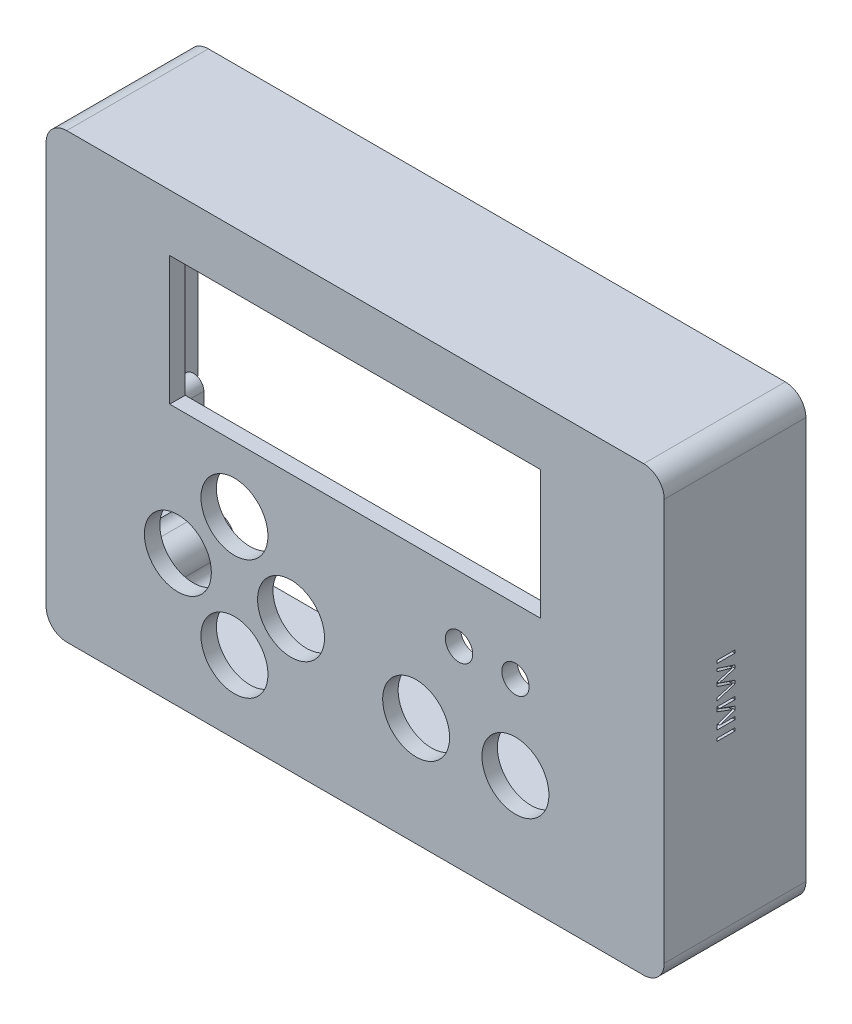
SolidWorks part; units mm, degrees
ref_plane "Front Plane" through (0, 0, 0) normal (0, 0, 1) x (1, 0, 0)
ref_plane "Top Plane" through (0, 0, 0) normal (0, 1, 0) x (1, 0, 0)
ref_plane "Right Plane" through (0, 0, 0) normal (1, 0, 0) x (0, 0, -1)
sketch "Sketch2" plane through (0, 0, 0) normal (0, 0, 1) x (1, 0, 0)
  line L0 (-36, 7) -> (36, 32) construction
  line L1 (-56, -43) -> (56, -43)
  line L2 (-60, -39) -> (-60, 39)
  line L3 (-56, 43) -> (56, 43)
  line L4 (60, -39) -> (60, 39)
  line L5 (-60, -43) -> (60, 43) construction
  line L7 (-36, 32) -> (36, 32)
  line L8 (-36, 32) -> (-36, 7)
  line L9 (-36, 7) -> (36, 7)
  line L10 (36, 32) -> (36, 7)
  line L11 (0, 43) -> (0, -43) construction
  line L12 (-23.4344, -5.6413) -> (-12.4484, -17.2736) construction
  line L13 (-12.4484, -17.2736) -> (-23.4344, -28.9058) construction
  line L14 (-23.4344, -28.9058) -> (-34.4203, -17.2736) construction
  line L15 (-34.4203, -17.2736) -> (-23.4344, -5.6413) construction
  line L16 (-23.4344, -5.6413) -> (-23.4344, -28.9058) construction
  line L17 (-12.4484, -17.2736) -> (-34.4203, -17.2736) construction
  circle A0 centre (-23.4344, -5.6413) radius 6.5
  circle A1 centre (-12.4484, -17.2736) radius 6.5
  circle A2 centre (-34.4203, -17.2736) radius 6.5
  circle A3 centre (-23.4344, -28.9058) radius 6.5
  circle A4 centre (11.8343, -21.8914) radius 6.5
  circle A5 centre (31.1116, -21.8914) radius 6.5
  circle A6 centre (20.1586, -5.6413) radius 2.65
  circle A7 centre (31.1116, -5.6413) radius 2.65
  arc A8 (-56, -43) -> (-60, -39) centre (-56, -39) cw
  arc A9 (56, -43) -> (60, -39) centre (56, -39) ccw
  arc A10 (56, 43) -> (60, 39) centre (56, 39) cw
  arc A11 (-60, 39) -> (-56, 43) centre (-56, 39) cw
  point P0 (0, 0)
  point P20 (0, 19.5)
  point P29 (0, 0)
  point P30 (0, 0)
  point P46 (60, -43)
  dimension "D3" = 72
  dimension "D6" = 11
  dimension "D7" = 4
  dimension "D1" = 86
  dimension "D2" = 120
  dimension "D4" = 25
  dimension "D5" = 16
extrude "Boss-Extrude1" add sketch "Sketch2" along normal blind 2.5
sketch "Sketch3" plane through (0, 0, 0) normal (0, 0, -1) x (-1, 0, 0)
  line L0 (60, 39) -> (60, -39) construction
  line L1 (56, -43) -> (-56, -43) construction
  line L2 (-60, -39) -> (-60, 39) construction
  line L3 (-56, 43) -> (56, 43) construction
  line L4 (60, 39) -> (60, -39)
  line L5 (56, -43) -> (-56, -43)
  line L6 (-60, -39) -> (-60, 39)
  line L7 (-56, 43) -> (56, 43)
  line L9 (-54, 41) -> (54, 41)
  line L10 (-58, 37) -> (-58, -37)
  line L11 (-54, -41) -> (54, -41)
  line L12 (58, 37) -> (58, -37)
  line L13 (-58, 41) -> (58, -41) construction
  line L14 (-58, -41) -> (58, 41) construction
  arc A0 (60, 39) -> (56, 43) centre (56, 39) ccw construction
  arc A1 (56, -43) -> (60, -39) centre (56, -39) ccw construction
  arc A2 (-60, -39) -> (-56, -43) centre (-56, -39) ccw construction
  arc A3 (-56, 43) -> (-60, 39) centre (-56, 39) ccw construction
  arc A4 (60, 39) -> (56, 43) centre (56, 39) ccw
  arc A5 (56, -43) -> (60, -39) centre (56, -39) ccw
  arc A6 (-60, -39) -> (-56, -43) centre (-56, -39) ccw
  arc A7 (-56, 43) -> (-60, 39) centre (-56, 39) ccw
  arc A8 (-58, 37) -> (-54, 41) centre (-54, 37) cw
  arc A9 (-58, -37) -> (-54, -41) centre (-54, -37) ccw
  arc A10 (58, -37) -> (54, -41) centre (54, -37) cw
  arc A11 (54, 41) -> (58, 37) centre (54, 37) cw
  point P3 (0, 0)
  dimension "D5" = 4
  dimension "D1" = 2
  dimension "D2" = 2
  dimension "D3" = 2
  dimension "D4" = 2
extrude "Boss-Extrude2" add sketch "Sketch3" along normal blind 25
sketch "Sketch5" plane through (0, 0, 0) normal (0, 0, -1) x (-1, 0, 0)
  line L0 (-36, 7) -> (-36, 32) construction
  line L1 (36, 7) -> (-36, 7) construction
  line L2 (36, 32) -> (36, 7) construction
  line L3 (-36, 32) -> (36, 32) construction
  line L4 (-36, 7) -> (-36, 32)
  line L5 (36, 7) -> (-36, 7)
  line L6 (36, 32) -> (36, 7)
  line L7 (-36, 32) -> (36, 32)
  line L9 (-37, 33) -> (37, 33)
  line L10 (-37, 33) -> (-37, 6)
  line L11 (-37, 6) -> (37, 6)
  line L12 (37, 33) -> (37, 6)
  circle A0 centre (23.4344, -28.9058) radius 6.5 construction
  circle A1 centre (34.4203, -17.2736) radius 6.5 construction
  circle A2 centre (23.4344, -5.6413) radius 6.5 construction
  circle A3 centre (12.4484, -17.2736) radius 6.5 construction
  circle A4 centre (-11.8343, -21.8914) radius 6.5 construction
  circle A5 centre (-20.1586, -5.6413) radius 2.65 construction
  circle A6 centre (-31.1116, -5.6413) radius 2.65 construction
  circle A7 centre (-31.1116, -21.8914) radius 6.5 construction
  circle A8 centre (23.4344, -28.9058) radius 6.5
  circle A9 centre (34.4203, -17.2736) radius 6.5
  circle A10 centre (23.4344, -5.6413) radius 6.5
  circle A11 centre (12.4484, -17.2736) radius 6.5
  circle A12 centre (-11.8343, -21.8914) radius 6.5
  circle A13 centre (-20.1586, -5.6413) radius 2.65
  circle A14 centre (-31.1116, -5.6413) radius 2.65
  circle A15 centre (-31.1116, -21.8914) radius 6.5
  circle A16 centre (-31.1116, -5.6413) radius 3.75
  circle A17 centre (-20.1586, -5.6413) radius 3.75
  circle A18 centre (-31.1116, -21.8914) radius 7.5
  circle A19 centre (-11.8343, -21.8914) radius 7.5
  circle A20 centre (12.4484, -17.2736) radius 7.5
  circle A21 centre (23.4344, -5.6413) radius 7.5
  circle A22 centre (34.4203, -17.2736) radius 7.5
  circle A23 centre (23.4344, -28.9058) radius 7.5
  dimension "D1" = 1
  dimension "D2" = 1
  dimension "D3" = 1
  dimension "D4" = 1
extrude "Boss-Extrude3" add sketch "Sketch5" along normal blind 0.5
sketch "Sketch6" plane through (0, 0, 0) normal (0, 0, -1) x (-1, 0, 0)
  line L0 (37.875, 41) -> (37.875, -41) construction
  line L1 (54, 41) -> (-54, 41) construction
  line L2 (-54, -41) -> (54, -41) construction
  line L3 (-37.875, -41) -> (-37.875, 41) construction
  line L4 (0, 41) -> (0, -39.2896) construction
  line L5 (37.875, 35) -> (37.875, 37) construction
  line L6 (37.125, 35) -> (37.125, 37)
  line L7 (38.625, 35) -> (38.625, 37)
  line L9 (-34.4881, 20) -> (37.5119, 20) construction
  line L12 (37.875, 38) -> (37.875, 34) construction
  line L13 (39.875, 38) -> (39.875, 34)
  line L14 (35.875, 38) -> (35.875, 34)
  line L15 (37.875, 2) -> (37.875, 6) construction
  line L16 (39.875, 2) -> (39.875, 6)
  line L17 (35.875, 2) -> (35.875, 6)
  line L18 (37.875, 5) -> (37.875, 3) construction
  line L19 (37.125, 5) -> (37.125, 3)
  line L20 (38.625, 5) -> (38.625, 3)
  line L21 (-37.875, 5) -> (-37.875, 3) construction
  line L22 (-37.125, 5) -> (-37.125, 3)
  line L23 (-38.625, 5) -> (-38.625, 3)
  line L24 (-37.875, 2) -> (-37.875, 6) construction
  line L25 (-39.875, 2) -> (-39.875, 6)
  line L26 (-35.875, 2) -> (-35.875, 6)
  line L27 (-37.875, 35) -> (-37.875, 37) construction
  line L28 (-37.125, 35) -> (-37.125, 37)
  line L29 (-38.625, 35) -> (-38.625, 37)
  line L30 (-37.875, 38) -> (-37.875, 34) construction
  line L31 (-39.875, 38) -> (-39.875, 34)
  line L32 (-35.875, 38) -> (-35.875, 34)
  line L33 (-36, 32) -> (36, 32) construction
  line L34 (36, 7) -> (-36, 7) construction
  arc A0 (37.125, 35) -> (38.625, 35) centre (37.875, 35) ccw
  arc A1 (38.625, 37) -> (37.125, 37) centre (37.875, 37) ccw
  arc A2 (39.875, 38) -> (35.875, 38) centre (37.875, 38) ccw
  arc A3 (35.875, 34) -> (39.875, 34) centre (37.875, 34) ccw
  arc A4 (39.875, 2) -> (35.875, 2) centre (37.875, 2) cw
  arc A5 (35.875, 6) -> (39.875, 6) centre (37.875, 6) cw
  arc A6 (37.125, 5) -> (38.625, 5) centre (37.875, 5) cw
  arc A7 (38.625, 3) -> (37.125, 3) centre (37.875, 3) cw
  arc A8 (-37.125, 5) -> (-38.625, 5) centre (-37.875, 5) ccw
  arc A9 (-38.625, 3) -> (-37.125, 3) centre (-37.875, 3) ccw
  arc A10 (-39.875, 2) -> (-35.875, 2) centre (-37.875, 2) ccw
  arc A11 (-35.875, 6) -> (-39.875, 6) centre (-37.875, 6) ccw
  arc A12 (-37.125, 35) -> (-38.625, 35) centre (-37.875, 35) cw
  arc A13 (-38.625, 37) -> (-37.125, 37) centre (-37.875, 37) cw
  arc A14 (-39.875, 38) -> (-35.875, 38) centre (-37.875, 38) cw
  arc A15 (-35.875, 34) -> (-39.875, 34) centre (-37.875, 34) cw
  point P12 (37.875, 36)
  point P25 (37.875, 36)
  point P32 (37.875, 4)
  point P39 (37.875, 4)
  point P46 (-37.875, 4)
  point P53 (-37.875, 4)
  point P60 (-37.875, 36)
  point P67 (-37.875, 36)
  dimension "D4" = 0.75
  dimension "D5" = 2
  dimension "D1" = 75.75
  dimension "D2" = 37.875
  dimension "D3" = 2
  dimension "D6" = 4
  dimension "D7" = 4
  dimension "D8" = 3
extrude "Boss-Extrude4" add sketch "Sketch6" along normal blind 4
sketch "Sketch7" plane through (0, 0, 0) normal (0, 0, -1) x (-1, 0, 0)
  line L0 (0, 41) -> (0, -41) construction
  line L1 (54, 41) -> (-54, 41) construction
  line L2 (-54, -41) -> (54, -41) construction
  line L3 (-58, 0) -> (58, 0) construction
  line L4 (-58, 37) -> (-58, -37) construction
  line L5 (58, -37) -> (58, 37) construction
  line L6 (54, 41) -> (-54, 41) construction
  line L7 (58, -37) -> (58, 37)
  line L8 (54, 41) -> (-54, 41)
  line L9 (-58, -37) -> (-58, 37)
  circle A0 centre (54.5, 37.5) radius 1.7
  arc A1 (53.3, 41) -> (58, 36.3) centre (54.5, 37.5) ccw
  arc A2 (58, 37) -> (54, 41) centre (54, 37) ccw construction
  arc A3 (58, 37) -> (54, 41) centre (54, 37) ccw
  circle A4 centre (54.5, -37.5) radius 1.7
  arc A5 (53.3, -41) -> (58, -36.3) centre (54.5, -37.5) cw
  arc A6 (-53.3, -41) -> (-58, -36.3) centre (-54.5, -37.5) ccw
  circle A7 centre (-54.5, -37.5) radius 1.7
  arc A8 (-58, 37) -> (-54, 41) centre (-54, 37) cw
  arc A9 (-53.3, 41) -> (-58, 36.3) centre (-54.5, 37.5) cw
  circle A10 centre (-54.5, 37.5) radius 1.7
  arc A11 (54, -41) -> (58, -37) centre (54, -37) ccw construction
  arc A12 (-58, -37) -> (-54, -41) centre (-54, -37) ccw construction
  arc A13 (54, -41) -> (58, -37) centre (54, -37) ccw
  arc A14 (-58, -37) -> (-54, -41) centre (-54, -37) ccw
  point P15 (54.301, 37.6033)
  arc M8 (-54, 41) -> (-58, 37) centre (-54, 37) ccw
  line M9 (-58, 37) -> (-58, -37)
  arc M10 (-58, -37) -> (-54, -41) centre (-54, -37) ccw
  line M11 (-54, -41) -> (54, -41)
  arc M12 (54, -41) -> (58, -37) centre (54, -37) ccw
  line M13 (58, -37) -> (58, 37)
  arc M14 (58, 37) -> (54, 41) centre (54, 37) ccw
  line M15 (54, 41) -> (-54, 41)
  dimension "D1" = 54.5
  dimension "D2" = 37.5
extrude "Boss-Extrude6" add sketch "Sketch7" along normal up to surface (25 mm away) contours A5 A4 M11 M12 M13 | A1 L7 A0 M15 M14 | A9 A10 M15 M8 M9 | A6 L9 A7 M11 M10 up to face at (0, 0, -25)
fillet "Fillet2" radius 2 8 edges at (-53.3, -41, -12.5) (-58, -36.3, -12.5) (53.3, -41, -12.5) (58, -36.3, -12.5) (53.3, 41, -12.5) (58, 36.3, -12.5) (-53.3, 41, -12.5) (-58, 36.3, -12.5)
sketch "Sketch8" plane through (-60, 0, 0) normal (-1, 0, 0) x (0, 0, 1)
  line L0 (-25, -39) -> (-25, 39) construction
  line L1 (-25, -33) -> (-15, -33)
  line L2 (-25, -33) -> (-25, -13)
  line L3 (-25, -13) -> (-15, -13)
  line L4 (-15, -33) -> (-15, -13)
  line L5 (2.5, -43) -> (-25, -43) construction
  dimension "D1" = 20
  dimension "D2" = 10
  dimension "D3" = 10
extrude "Cut-Extrude1" cut sketch "Sketch8" against normal up to next
sketch "Sketch9" plane through (60, 0, 0) normal (1, 0, 0) x (0, 0, -1)
  line L0 (11.25, -39) -> (11.25, 39) construction
  line L1 (-2.5, -39) -> (25, -39) construction
  line L2 (-2.5, 39) -> (25, 39) construction
  text T0 "IMWI" font "Century Gothic" height 3.5
  point P3 (15.4983, 12.9039)
  point P4 (16.0515, -16.6346)
  point P5 (11.4294, 28.6507)
  point P6 (12.2848, -4.235)
  point P7 (12.2278, -24.3219)
  point P8 (12.4022, -13.392)
  point P9 (12.447, 12.6028)
  point P10 (12.4644, 4.1349)
  point P11 (12.5605, 5.3166)
  point P12 (13.8206, -21.1347)
  point P13 (20.4156, 33.8816)
  point P14 (21.647, -39)
  point P17 (21.1497, 39)
  point P20 (11.25, 39)
extrude "Cut-Extrude2" cut sketch "Sketch9" against normal blind 0.75
